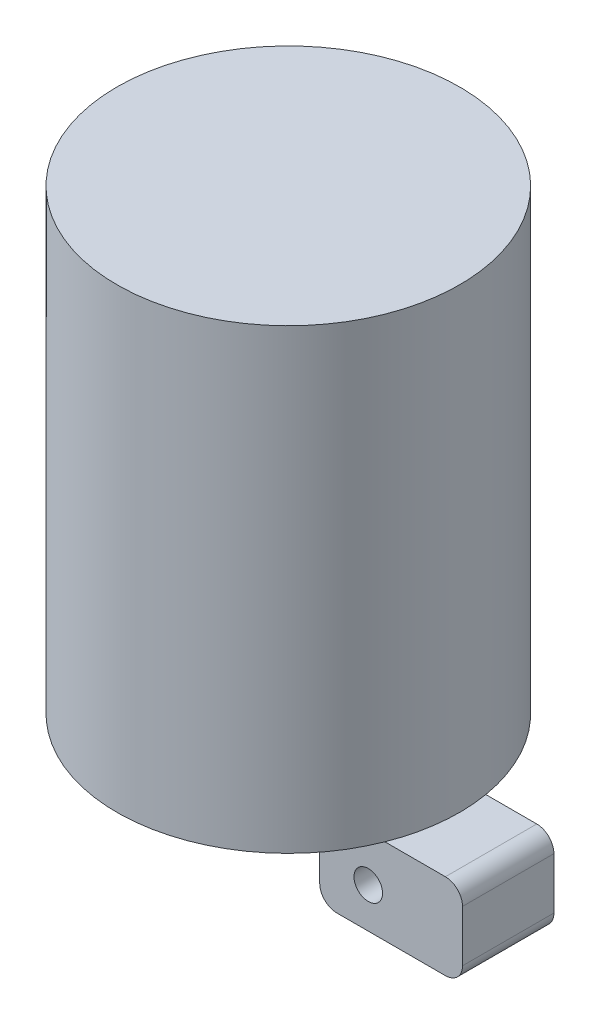
SolidWorks part; units mm, degrees
ref_plane "Front Plane" through (0, 0, 0) normal (0, 0, 1) x (1, 0, 0)
ref_plane "Top Plane" through (0, 0, 0) normal (0, 1, 0) x (1, 0, 0)
ref_plane "Right Plane" through (0, 0, 0) normal (1, 0, 0) x (0, 0, -1)
sketch "Sketch1" plane through (0, 0, 0) normal (0, 0, 1) x (1, 0, 0)
  line L0 (0, 0) -> (0, 80)
  line L1 (0, 80) -> (60, 80)
  line L2 (60, 80) -> (60, 0)
  line L3 (0, 0) -> (17.5, 0)
  line L4 (17.5, 0) -> (42.5, 0)
  line L5 (17.5, 0) -> (17.5, 40)
  line L6 (17.5, 40) -> (42.5, 40)
  line L7 (42.5, 0) -> (42.5, 40)
  line L8 (42.5, 0) -> (60, 0)
  line L9 (30, 80) -> (30, 40) construction
  point P3 (30, 40)
  point P6 (30, 80)
  dimension "D1" = 60
  dimension "D2" = 80
  dimension "D3" = 40
  dimension "D4" = 25
revolve "Revolve1" add sketch "Sketch1" angle 360 about L9
sketch "Sketch2" plane through (0, 0, 0) normal (0, 0, 1) x (1, 0, 0)
  line L0 (46.5, 0) -> (46.5, -12)
  line L1 (49.5, -15) -> (68.5, -15)
  line L2 (71.5, -12) -> (71.5, -3)
  line L5 (68.5, 0) -> (46.5, 0)
  line L6 (17.5, 0) -> (42.5, 0) construction
  circle A0 centre (55, -8) radius 2.5
  arc A1 (71.5, -3) -> (68.5, 0) centre (68.5, -3) ccw
  arc A2 (68.5, -15) -> (71.5, -12) centre (68.5, -12) ccw
  arc A3 (46.5, -12) -> (49.5, -15) centre (49.5, -12) ccw
  point P16 (71.5, -15)
  point P19 (46.5, -15)
  dimension "D6" = 55
  dimension "D7" = 5
  dimension "D4" = 3
  dimension "D1" = 8.5
  dimension "D2" = 25
  dimension "D3" = 15
  dimension "D8" = 8
extrude "Boss-Extrude5" add sketch "Sketch2" along normal blind 11 and the other way blind 5
